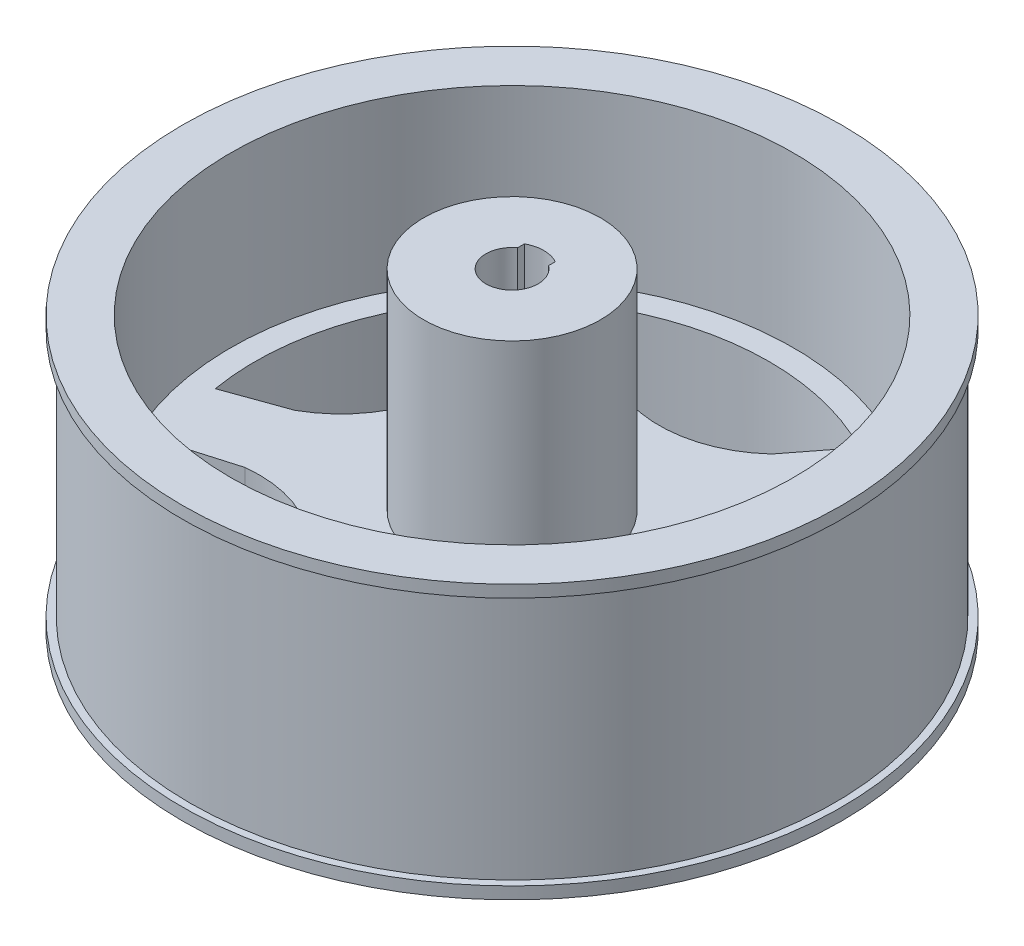
SolidWorks part; units mm, degrees
material "ABS"
ref_plane "Front Plane" through (0, 0, 0) normal (0, 0, 1) x (1, 0, 0)
ref_plane "Top Plane" through (0, 0, 0) normal (0, 1, 0) x (1, 0, 0)
ref_plane "Right Plane" through (0, 0, 0) normal (1, 0, 0) x (0, 0, -1)
sketch "Sketch1" plane through (0, 0, 0) normal (0, 1, 0) x (1, 0, 0)
  circle A0 centre (0, 0) radius 41
  dimension "D1" = 82
extrude "Boss-Extrude1" add sketch "Sketch1" along normal blind 34
sketch "Sketch2" plane through (0, 34, 0) normal (0, 1, 0) x (1, 0, 0)
  circle A0 centre (0, 0) radius 35
  dimension "D1" = 70
extrude "Cut-Extrude1" cut sketch "Sketch2" against normal blind 21
sketch "Sketch3" plane through (0, 0, 0) normal (0, -1, 0) x (1, 0, 0)
  line L0 (-4.6328, 31.6629) -> (-4.8756, 23.8937)
  line L1 (-28.6816, 14.1904) -> (-21.2252, 12.0151)
  line L2 (28.6816, 14.1904) -> (21.2176, 12.0205)
  line L3 (4.6328, 31.6629) -> (4.8681, 23.8992)
  line L4 (22.359, -22.8927) -> (17.9888, -16.4646)
  line L5 (31.5448, 5.3783) -> (24.2338, 2.7554)
  line L6 (-14.863, -28.3389) -> (-10.0999, -22.1962)
  line L7 (-31.5448, 5.3783) -> (-24.2309, 2.7466)
  line L8 (14.863, -28.3389) -> (10.1092, -22.1962)
  line L9 (-22.359, -22.8927) -> (-17.986, -16.4735)
  arc A0 (-31.5448, 5.3783) -> (-22.359, -22.8927) centre (0, 0) ccw
  arc A1 (-24.2309, 2.7466) -> (-17.986, -16.4735) centre (-31.5833, -10.2669) cw
  arc A2 (-4.6328, 31.6629) -> (-28.6816, 14.1904) centre (0, 0) ccw
  arc A3 (-4.8756, 23.8937) -> (-21.2252, 12.0151) centre (-19.5242, 26.8649) cw
  arc A4 (28.6816, 14.1904) -> (4.6328, 31.6629) centre (0, 0) ccw
  arc A5 (21.2176, 12.0205) -> (4.8681, 23.8992) centre (19.5167, 26.8703) cw
  arc A6 (22.359, -22.8927) -> (31.5448, 5.3783) centre (0, 0) ccw
  arc A7 (17.9888, -16.4646) -> (24.2338, 2.7554) centre (31.5862, -10.2581) cw
  arc A8 (-14.863, -28.3389) -> (14.863, -28.3389) centre (0, 0) ccw
  arc A9 (-10.0999, -22.1962) -> (10.1092, -22.1962) centre (0.0046, -33.2102) cw
  point P29 (0, 0)
  dimension "D1" = 32
  dimension "D2" = 14.9469
extrude "Cut-Extrude2" cut sketch "Sketch3" against normal blind 21
sketch "Sketch5" plane through (0, 0, 0) normal (0, 0, 1) x (1, 0, 0)
  line L0 (28, 0) -> (32, 0)
  line L1 (-41, 0) -> (41, 0) construction
  line L2 (32, 0) -> (32, 4)
  line L3 (0, 0) -> (0, 2.5)
  line L4 (0, 2.5) -> (9, 2.5)
  line L5 (9, 2.5) -> (9, 4)
  line L6 (9, 4) -> (12.5, 4)
  line L7 (0, 0) -> (14, 0)
  line L8 (14, 0) -> (12.5, 4)
  arc A0 (28, 0) -> (32, 4) centre (28, 4) ccw
  dimension "D1" = 4
  dimension "D2" = 4
  dimension "D3" = 4
  dimension "D8" = 4
  dimension "D4" = 9
  dimension "D5" = 1.5
  dimension "D6" = 1.5
  dimension "D7" = 14
  dimension "D9" = 14
revolve "Cut-Revolve1" cut sketch "Sketch5" angle 360 about axis through (0, 34, 0) along (0, -1, 0)
sketch "Sketch6" plane through (0, 13, 0) normal (0, 1, 0) x (1, 0, 0)
  circle A0 centre (0, 0) radius 11
  dimension "D1" = 22
extrude "Boss-Extrude2" add sketch "Sketch6" along normal blind 26
sketch "Esboço1" plane through (0, 39, 0) normal (0, 1, 0) x (1, 0, 0)
  circle A0 centre (0, 0) radius 3.25
  dimension "D1" = 6.5
extrude "Corte-extrusão1" cut sketch "Esboço1" against normal blind 15
sketch "Esboço2" plane through (0, 0, 0) normal (0, 0, 1) x (1, 0, 0)
  line L0 (-41, 1.5) -> (-41, 32.5)
  line L2 (-41, 32.5) -> (-40.1, 32.5)
  line L3 (-40.1, 32.5) -> (-40.1, 1.5)
  line L4 (-40.1, 1.5) -> (-41, 1.5)
  line L5 (0, -9.5123) -> (0, 41.2888) construction
  line L6 (0, 34) -> (0, 0) construction
  line L7 (-41, 0) -> (41, 0) construction
  point P6 (-41, 17)
  dimension "D1" = 31
  dimension "D2" = 0.9
  dimension "D3" = 40.1
  dimension "D4" = 1.5
revolve "Corte-Revolução1" cut sketch "Esboço2" angle 360 about L5
sketch "Esboço3" plane through (0, 39, 0) normal (0, 1, 0) x (1, 0, 0)
  line L0 (-1.925, 2.6186) -> (-1.925, 3.4492)
  line L1 (0, 3.25) -> (0, 3.95) construction
  line L3 (1.925, 2.6186) -> (1.925, 3.4492)
  circle A2 centre (0, 0) radius 3.25 construction
  arc A3 (1.925, 3.4492) -> (-1.925, 3.4492) centre (0, 0) ccw
  arc A4 (1.925, 2.6186) -> (-1.925, 2.6186) centre (0, 0) ccw
  circle A5 centre (0, 0) radius 3.25 construction
  circle A6 centre (0, 0) radius 3.25 construction
  dimension "D1" = 3.85
  dimension "D2" = 0.7
extrude "Corte-extrusão4" cut sketch "Esboço3" against normal blind 12.8
